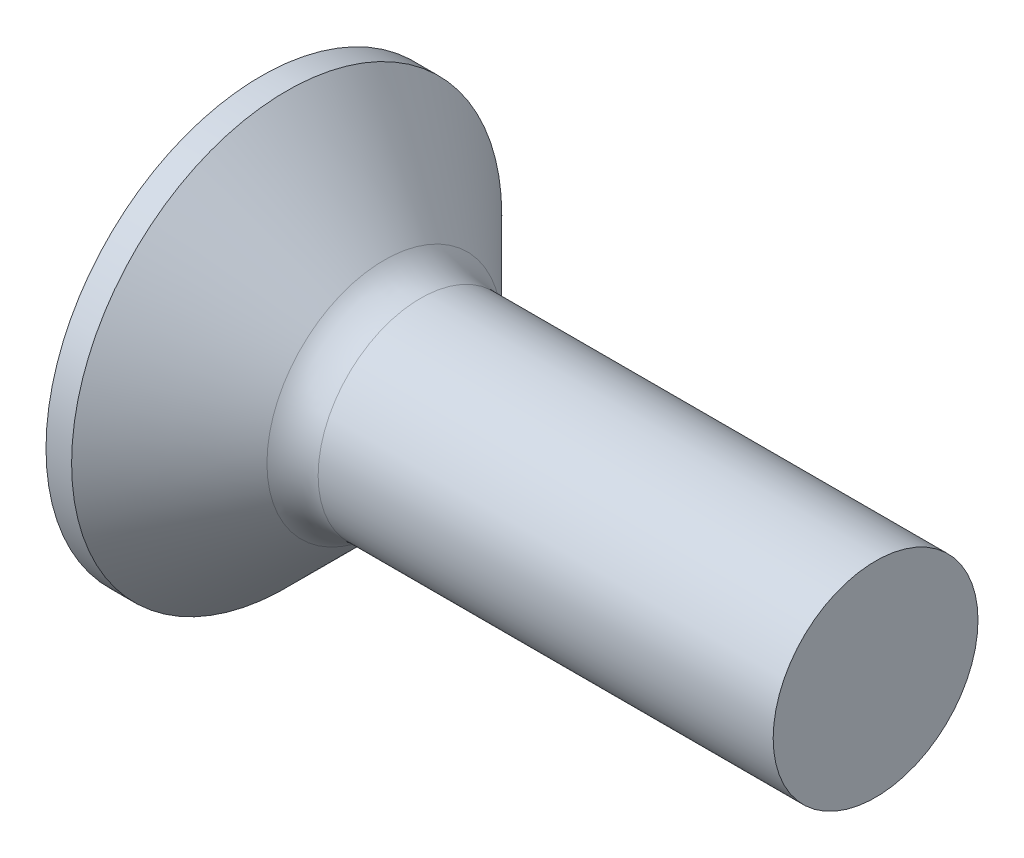
SolidWorks part; units mm, degrees
revolve "Base-Revolve" add sketch "BodySke"
sketch "BodySke" plane through (0, 0, 0) normal (0, 0, 1) x (1, 0, 0)
  line L0 (0, 0) -> (0, 4.2)
  line L1 (0, 4.2) -> (0.5, 4.2)
  line L2 (2.7, 2) -> (12, 2)
  line L3 (12, 2) -> (12, 0)
  line L4 (12, 0) -> (0, 0)
  line L5 (-6.35, 0) -> (82.55, 0) construction
  line L6 (2.7, -2) -> (12, -2) construction
  line L7 (0.5, -4.2) -> (2.7, -2) construction
  line L8 (0.5, 4.2) -> (2.7, 2)
  line L9 (0, -4.2) -> (0.5, -4.2) construction
  line L10 (3.4, 3.5875) -> (3.4, -5.9375) construction
  line L11 (0, 6.35) -> (0, -3.175) construction
  dimension "Diameter" = 4
  dimension "Length" = 12
  dimension "Head_ht" = 2.7
  dimension "Head_dia" = 8.4
  dimension "Head_ang" = 90
  dimension "D6" = 0.5
  dimension "Advance" = 0.7
  dimension "Thread_nom" = 12
cosmetic thread "ThreadCosmetic" [suppressed]
fillet "Fillet1" radius 1 1 edges at (2.7, 0, 2)
material "Plain Carbon Steel"
ref_plane "Plane1" through (0, 0, 0) normal (0, 0, 1) x (1, 0, 0)
ref_plane "Plane2" through (0, 0, 0) normal (0, 1, 0) x (1, 0, 0)
ref_plane "Plane3" through (0, 0, 0) normal (1, 0, 0) x (0, 0, -1)
other "Configuration Table"
sketch "Sketch3" plane through (0, 0, 0) normal (-1, 0, 0) x (0, 0, 1)
  line L0 (-0.515, 2.2) -> (0.515, 2.2)
  line L1 (0.515, 2.2) -> (0.515, -2.2)
  line L2 (0.515, -2.2) -> (-0.515, -2.2)
  line L3 (-0.515, -2.2) -> (-0.515, 2.2)
  dimension "Cross_dia" = 4.4
  dimension "Cross_width" = 1.03
  dimension "D1" = 2.2
  dimension "D2" = 0.515
ref_plane "Plane4" through (2.51, 0, 0) normal (-1, 0, 0) x (0, 0, 1)
sketch "Sketch4" plane through (2.51, 0, 0) normal (-1, 0, 0) x (0, 0, 1)
  line L0 (-0.515, 0.9486) -> (0.515, 0.9486)
  line L3 (0.515, 0.9486) -> (0.515, -0.9486)
  line L4 (0.515, -0.9486) -> (-0.515, -0.9486)
  line L5 (-0.515, -0.9486) -> (-0.515, 0.9486)
  dimension "D2" = 1.8971
  dimension "D1" = 1.03
  dimension "D4" = 0.9486
  dimension "D3" = 0.515
loft "Recess" cut profiles "Sketch3", "Sketch4"
pattern_circular "RecPat" count 2 every 90 about axis through (0, 0, 0) along (1, 0, 0) of "Recess"
sketch "RecCorSke" plane through (0, 0, 0) normal (0, 0, 1) x (1, 0, 0)
  line L0 (-3.175, 0) -> (15.875, 0) construction
  line L2 (0, 0) -> (0, 1.0265)
  line L3 (0, 1.0265) -> (2.51, 0.851)
  line L4 (2.51, 0.851) -> (2.7865, 0)
  line L5 (2.7865, 0) -> (0, 0)
  dimension "Diameter" = 1.702
  dimension "Depth" = 2.51
  dimension "Draft_angle" = 4
  dimension "Bottom_angle" = 18
revolve "RecessCore" cut sketch "RecCorSke" angle 360 about L0
sketch "ThdSchSke" plane through (0, 0, 0) normal (0, 0, 1) x (1, 0, 0)
  line L0 (3.4, -1.61) -> (3.1269, -2)
  line L1 (3.4, -1.61) -> (3.6731, -2)
  line L2 (3.6731, -2) -> (3.6731, -2.5)
  line L3 (-3.175, 0) -> (5.1513, 0) construction
  line L5 (3.6731, -2.5) -> (3.1269, -2.5)
  line L6 (3.1269, -2.5) -> (3.1269, -2)
  line L7 (0, 4.2) -> (0, -4.2) construction
  dimension "Diameter" = 4
  dimension "Thread_minor" = 3.22
  dimension "Start" = 3.4
revolve "ThreadSchematic" [suppressed] cut sketch "ThdSchSke" angle 360 about L3
pattern_linear "ThdSchPat" [suppressed]
equation "\"D1@Sketch3\" = \"Cross_dia@Sketch3\" / 2"
equation "\"D2@Sketch3\" = \"Cross_width@Sketch3\" / 2"
equation "\"Depth@RecCorSke\" = \"Cross_depth@Plane4\""
equation "\"D1@Sketch4\" = \"Cross_width@Sketch3\""
equation "\"D2@Sketch4\" = \"Cross_dia@Sketch3\" - 2.0 * \"Cross_depth@Plane4\" * tan(26.5  * 0.017453292)"
equation "\"D3@Sketch4\" = \"D1@Sketch4\" / 2"
equation "\"D4@Sketch4\" = \"D2@Sketch4\" / 2"
equation "\"Thread_length@ThreadCosmetic\" = ((sgn( (\"Length@BodySke\" - \"Advance@BodySke\" * 1.0 - \"Head_ht@BodySke\" ) - \"Thread_nom@BodySke\" )-1)*( (\"Length@BodySke\" - \"Advance@BodySke\" * 1.0 - \"Head_ht@BodySke\" ) - \"Thread_nom@BodySke\" ))/-2+ \"Thread_nom@BodySke\""
equation "\"Thread_minor@ThdSchSke\" = \"Thread_minor@ThreadCosmetic\""
equation "\"Diameter@ThdSchSke\" = \"Diameter@BodySke\""
equation "\"Overcut@ThdSchSke\" = \"Diameter@BodySke\" * 1.25"
equation "\"Start@ThdSchSke\" = 0.000001 + \"Length@BodySke\" - \"Thread_length@ThreadCosmetic\"  '---Countersunk---"
equation "\"Num_threads@ThdSchPat\" = int( \"Thread_length@ThreadCosmetic\" / \"Advance@BodySke\" + 0.999 )  + 1"
equation "\"Advance@ThdSchPat\" = \"Thread_length@ThreadCosmetic\" /  (\"Num_threads@ThdSchPat\" - 1) 'relax it"
